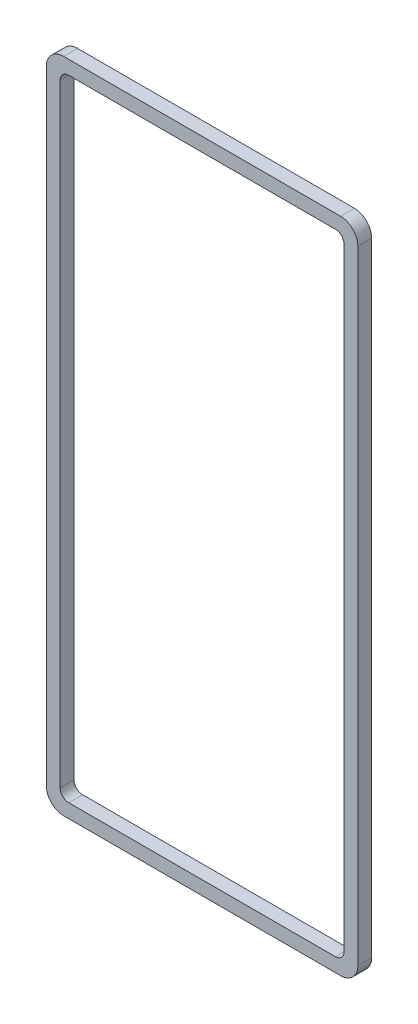
SolidWorks part; units mm, degrees
ref_plane "Plan de face" through (0, 0, 0) normal (0, 0, 1) x (1, 0, 0)
ref_plane "Plan de dessus" through (0, 0, 0) normal (0, 1, 0) x (1, 0, 0)
ref_plane "Plan de droite" through (0, 0, 0) normal (1, 0, 0) x (0, 0, -1)
sketch "Esquisse1" plane through (0, 0, 0) normal (0, 0, 1) x (1, 0, 0)
  line L0 (40, 40) -> (860, 40)
  line L1 (0, 0) -> (900, 0)
  line L2 (0, 0) -> (0, 1900)
  line L3 (0, 1900) -> (900, 1900)
  line L4 (900, 0) -> (900, 1900)
  line L5 (860, 40) -> (860, 1860)
  line L6 (40, 1860) -> (860, 1860)
  line L7 (40, 40) -> (40, 1860)
  dimension "D1" = 900
  dimension "D2" = 1900
  dimension "D3" = 40
extrude "Boss.-Extru.1" add sketch "Esquisse1" along normal blind 40
fillet "Congé1" radius 50 4 edges at (0, 0, 20) (900, 0, 20) (900, 1900, 20) (0, 1900, 20)
fillet "Congé2" radius 25 4 edges at (40, 1860, 20) (40, 40, 20) (860, 40, 20) (860, 1860, 20)
